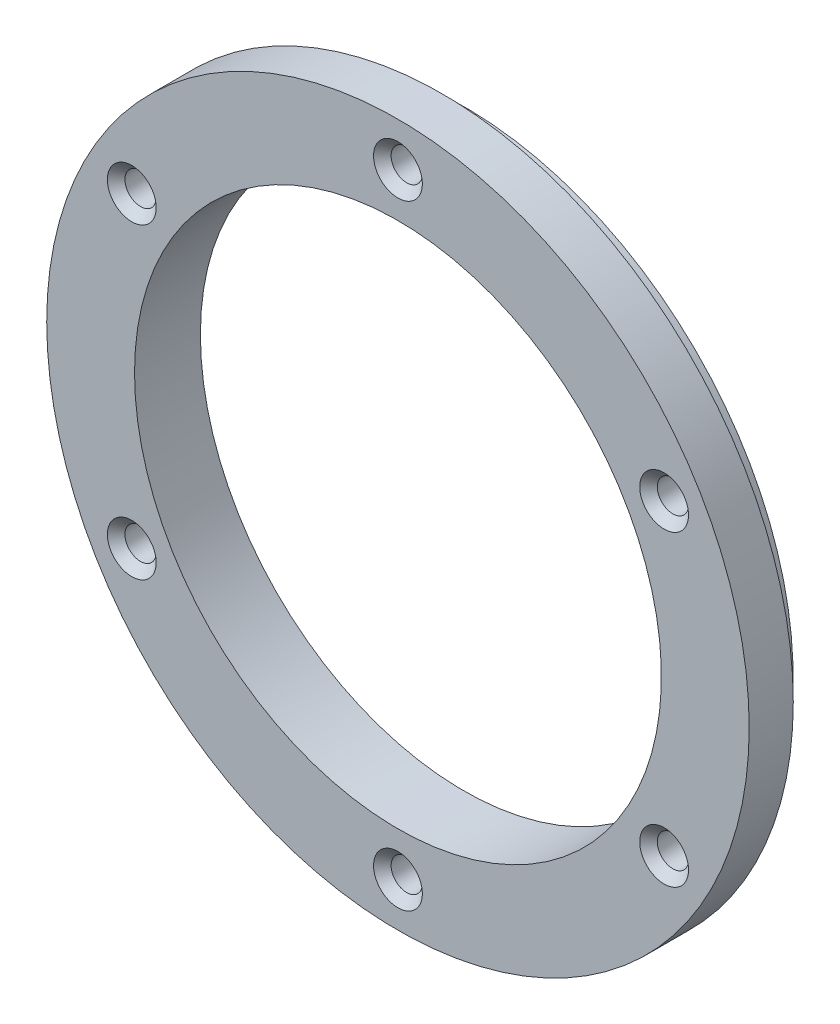
SolidWorks part; units mm, degrees
material "6061-T6 (SS)"
ref_plane "Front Plane" through (0, 0, 0) normal (0, 0, 1) x (1, 0, 0)
ref_plane "Top Plane" through (0, 0, 0) normal (0, 1, 0) x (1, 0, 0)
ref_plane "Right Plane" through (0, 0, 0) normal (1, 0, 0) x (0, 0, -1)
sketch "Sketch1" plane through (0, 0, 0) normal (0, 0, 1) x (1, 0, 0)
  circle A0 centre (0, 0) radius 25.4
  circle A1 centre (0, 0) radius 19.05
  dimension "D1" = 50.8
  dimension "D2" = 6.35
extrude "Boss-Extrude1" add sketch "Sketch1" along normal blind 4.7625
hole_wizard "#4-40 Tapped Hole1" positions "Sketch4" profile "Sketch3" tap size "#4-40" standard "Ansi Inch"
sketch "Sketch4" plane through (0, 0, 4.7625) normal (0, 0, 1) x (1, 0, 0)
  circle A0 centre (0, 0) radius 22.225 construction
  circle A1 centre (0, 0) radius 25.4 construction
  point P0 (0, 22.225)
  point P23 (-19.2474, 11.1125) [skipped]
  point P45 (19.2474, 11.1125)
  point P46 (19.2474, -11.1125)
  point P47 (0, -22.225)
  point P48 (-19.2474, -11.1125)
  point P49 (-19.2474, 11.1125)
  dimension "D1" = 3.175
  dimension "D2" = 6
sketch "Sketch3" plane through (0, 22.225, 4.7625) normal (1, 0, 0) x (0, -1, 0)
  line L0 (0, 0) -> (0, 8.2992)
  line L1 (0, 8.2992) -> (1.1303, 7.62)
  line L2 (1.1303, 7.62) -> (1.1303, 0.635)
  line L3 (1.1303, 0.635) -> (1.7653, 0)
  line L5 (1.7653, 0) -> (0, 0)
  line L6 (-1.1303, 0.635) -> (-1.7653, 0) construction
  line L10 (0, 8.2992) -> (-1.1303, 7.62) construction
  line L11 (0, -6.35) -> (0, 107.95) construction
  dimension "Tap Drill Dia." = 2.2606
  dimension "Tap Drill Depth" = 7.62
  dimension "Near C'Sink Dia." = 3.5306
  dimension "Near C'Sink Angle" = 90
  dimension "Drill Angle" = 118
cosmetic thread "Hole Thread7" parameters "D1"=4.7625, "D2"=2.8448
cosmetic thread "Hole Thread8" parameters "D1"=4.7625, "D2"=2.8448
cosmetic thread "Hole Thread9" parameters "D1"=4.7625, "D2"=2.8448
cosmetic thread "Hole Thread10" parameters "D1"=4.7625, "D2"=2.8448
cosmetic thread "Hole Thread11" parameters "D1"=4.7625, "D2"=2.8448
cosmetic thread "Hole Thread12" parameters "D1"=4.7625, "D2"=2.8448
sketch "Sketch5" plane through (0, 0, 0) normal (0, 0, -1) x (-1, 0, 0)
  circle A0 centre (0, 0) radius 23.8125
  dimension "D1" = 47.625
extrude "Cut-Extrude1" cut sketch "Sketch5" against normal blind 1.5748 flip side to cut
